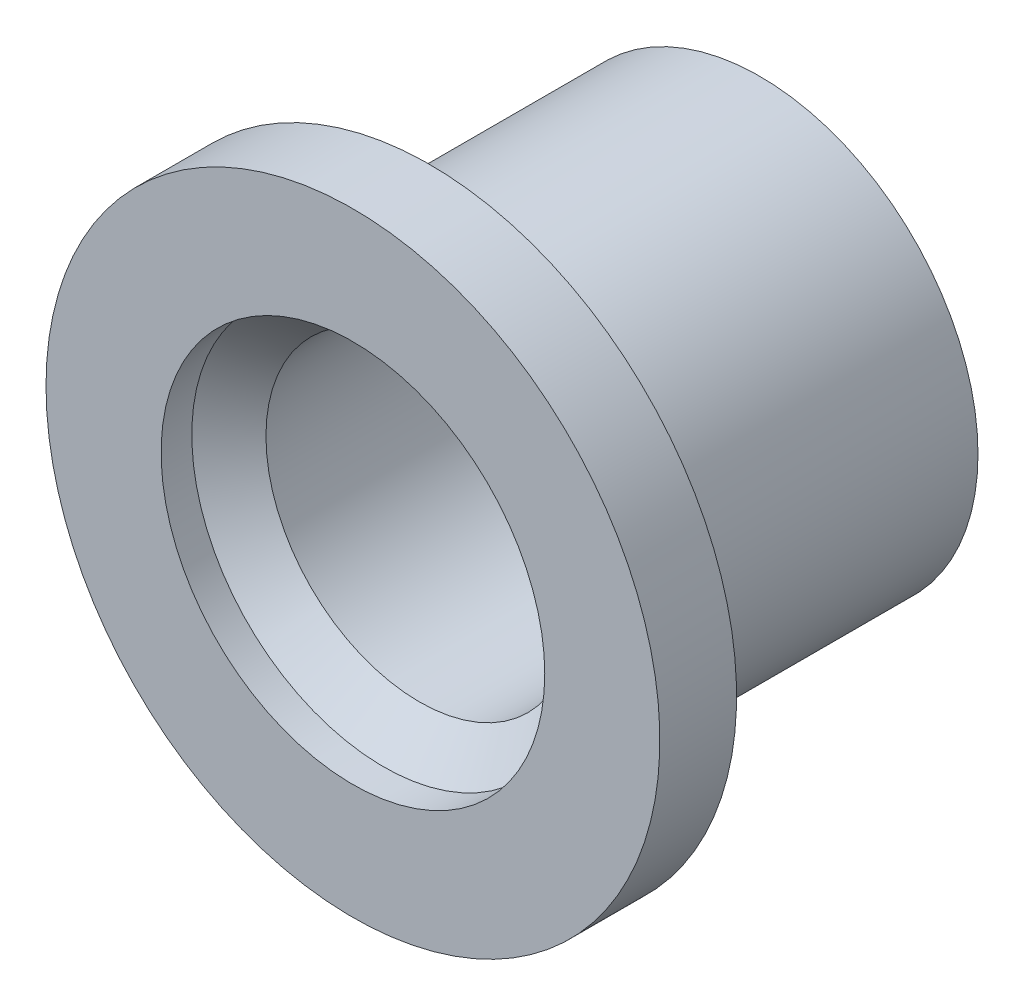
SolidWorks part; units mm, degrees
ref_plane "Front Plane" through (0, 0, 0) normal (0, 0, 1) x (1, 0, 0)
ref_plane "Top Plane" through (0, 0, 0) normal (0, 1, 0) x (1, 0, 0)
ref_plane "Right Plane" through (0, 0, 0) normal (1, 0, 0) x (0, 0, -1)
sketch "Sketch1" plane through (0, 0, 0) normal (0, 0, 1) x (1, 0, 0)
  circle A0 centre (0, 0) radius 5.08
  circle A1 centre (0, 0) radius 2.54
  dimension "D1" = 5.08
  dimension "D2" = 10.16
extrude "Boss-Extrude1" add sketch "Sketch1" along normal blind 0.762
chamfer "Chamfer2" distance 0.635 angle 43 1 edges at (2.54, 0, 0.762)
sketch "Sketch3" plane through (0, 0, 0.762) normal (0, 0, 1) x (1, 0, 0)
  circle A0 centre (0, 0) radius 3.175
  circle A1 centre (0, 0) radius 5.08
  dimension "D1" = 6.35
extrude "Boss-Extrude3" add sketch "Sketch3" along normal blind 0.508
sketch "Sketch4" plane through (0, 0, 0) normal (0, 0, -1) x (-1, 0, 0)
  circle A0 centre (0, 0) radius 2.54
  circle A1 centre (0, 0) radius 3.6094
extrude "Boss-Extrude4" add sketch "Sketch4" along normal offset from surface (5.4661 mm away) 0.127
sketch "Sketch5" plane through (0, 0, 0) normal (1, 0, 0) x (0, 0, -1)
  line L0 (-1.27, 0) -> (5.4661, 0) construction
  line L1 (-1.27, 5.08) -> (-1.27, -5.08) construction
  line L2 (5.4661, -3.6094) -> (5.4661, 3.6094) construction
